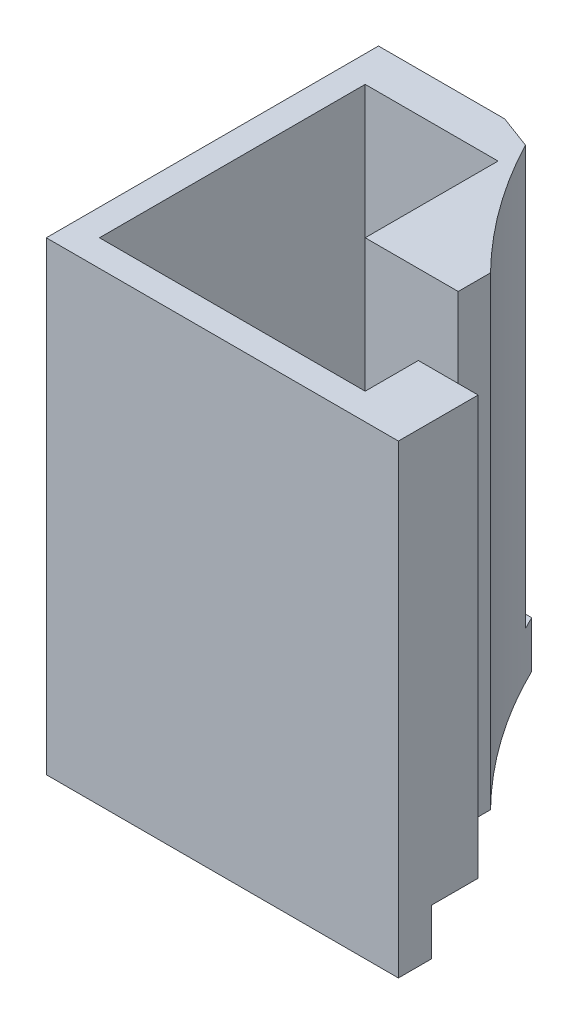
SolidWorks part; units mm, degrees
ref_plane "前视基准面" through (0, 0, 0) normal (0, 0, 1) x (1, 0, 0)
ref_plane "上视基准面" through (0, 0, 0) normal (0, 1, 0) x (1, 0, 0)
ref_plane "右视基准面" through (0, 0, 0) normal (1, 0, 0) x (0, 0, -1)
sketch "草图1" plane through (0, 0, 0) normal (0, 1, 0) x (1, 0, 0)
  line L1 (0, 0) -> (50, 0)
  line L2 (0, 0) -> (0, 50)
  line L3 (0, 50) -> (50, 50)
  line L4 (50, 0) -> (50, 50)
  dimension "D1" = 50
  dimension "D2" = 50
extrude "凸台-拉伸1" add sketch "草图1" along normal blind 7
sketch "草图2" plane through (0, 7, 0) normal (0, 1, 0) x (1, 0, 0)
  line L0 (95, 7) -> (95, 163)
  circle A0 centre (95, 85) radius 80
  dimension "D1" = 160
extrude "切除-拉伸1" cut sketch "草图2" against normal blind 10 contours A0
sketch "草图3" plane through (0, 7, 0) normal (0, 1, 0) x (1, 0, 0)
  line L0 (0, 50) -> (0, 0) construction
  line L1 (38, 35) -> (60, 35)
  line L2 (38, 35) -> (38, 5)
  line L3 (38, 5) -> (60, 5)
  line L4 (60, 35) -> (60, 5)
  line L5 (0, 0) -> (50, 0) construction
  dimension "D1" = 38
  dimension "D2" = 5
  dimension "D3" = 22
  dimension "D4" = 30
extrude "切除-拉伸2" cut sketch "草图3" against normal blind 10
hole_wizard "孔1" positions "草图4" profile "草图5" legacy end condition through all
sketch "草图4" plane through (0, 0, 0) normal (0, -1, 0) x (-1, 0, 0)
  point P0 (-32, 8)
  point P2 (-8, 8)
sketch "草图5" plane through (32, 0, -8) normal (1, 0, 0) x (0, 0, -1)
  line L0 (0, 0) -> (0, 7)
  line L1 (0, 7) -> (1.75, 7)
  line L2 (1.75, 7) -> (1.75, 0)
  line L3 (1.75, 0) -> (0, 0)
  line L4 (0, 110) -> (0, -10) construction
  dimension "直径" = 3.5
  dimension "深度" = 7
hole_wizard "孔2" positions "草图6" profile "草图7" legacy
sketch "草图6" plane through (0, 7, 0) normal (0, 1, 0) x (1, 0, 0)
  point P0 (8, 8)
  point P2 (32, 8)
sketch "草图7" plane through (8, 7, -8) normal (1, 0, 0) x (0, 0, 1)
  line L0 (0, 0) -> (0, 4)
  line L1 (0, 4) -> (3.5, 4)
  line L2 (3.5, 4) -> (3.5, 0)
  line L3 (3.5, 0) -> (0, 0)
  line L4 (0, 110) -> (0, -10) construction
  dimension "直径" = 7
  dimension "深度" = 4
sketch "草图8" plane through (0, 7, 0) normal (0, 1, 0) x (1, 0, 0)
  line L0 (0, 50) -> (0, 0) construction
  line L1 (4, 4) -> (44, 4)
  line L2 (4, 4) -> (4, 24)
  line L3 (4, 24) -> (44, 24)
  line L4 (44, 4) -> (44, 24)
  line L5 (0, 0) -> (50, 0) construction
  line L7 (4, 24) -> (24, 24)
  line L8 (4, 24) -> (4, 44)
  line L9 (4, 44) -> (24, 44)
  line L10 (24, 24) -> (24, 44)
  dimension "D1" = 40
  dimension "D2" = 20
  dimension "D3" = 4
  dimension "D4" = 4
  dimension "D5" = 20
  dimension "D6" = 20
sketch "草图9" plane through (0, 7, 0) normal (0, 1, 0) x (1, 0, 0)
  line L0 (0, 0) -> (50, 0) construction
  line L1 (0, 0) -> (4, 0)
  line L2 (0, 0) -> (0, 50)
  line L3 (0, 50) -> (4, 50)
  line L4 (4, 0) -> (4, 50)
  line L5 (23.0625, 50) -> (0, 50) construction
  line L6 (4, 44) -> (24, 44) construction
  line L7 (4, 0) -> (50, 0)
  line L8 (4, 0) -> (4, 4)
  line L9 (4, 4) -> (50, 4)
  line L10 (50, 0) -> (50, 4)
  line L11 (0, 50) -> (0, 0) construction
  line L12 (50, 0) -> (50, 5) construction
  line L13 (4, 4) -> (44, 4) construction
  line L14 (4, 50) -> (19, 50)
  line L15 (4, 50) -> (4, 44)
  line L16 (4, 44) -> (19, 44)
  line L17 (19, 50) -> (19, 44)
  line L18 (24, 48.1354) -> (24, 24)
  line L19 (24, 24) -> (38, 24)
  line L20 (38, 28.8662) -> (38, 5) construction
  line L21 (38, 24) -> (38, 28.8662)
  line L24 (4, 4) -> (4, 24) construction
  line L26 (24, 24) -> (24, 44) construction
  line L27 (4, 24) -> (44, 24) construction
  circle A1 centre (95, 85) radius 80
  line M15 (38, 5) -> (38, 28.8662)
  arc M16 (38, 28.8662) -> (23.0625, 50) centre (95, 85) cw
  line M17 (23.0625, 50) -> (0, 50)
  line M18 (0, 50) -> (0, 0)
  line M19 (0, 0) -> (50, 0)
  line M20 (50, 0) -> (50, 5)
  dimension "D7" = 160
  dimension "D5" = 95
  dimension "D6" = 85
  dimension "D9" = 15
extrude "凸台-拉伸2" add sketch "草图9" along normal blind 63 contours L17 L4 L16 M17 | L4 M19 M17 M18 | L9 L4 M19 M20 | L18 L19 M15 M16
sketch "草图10" plane through (0, 7, 0) normal (0, 1, 0) x (1, 0, 0)
  line L0 (50, 4) -> (50, 5) construction
  line L1 (50, 4) -> (44, 4)
  line L2 (50, 4) -> (50, 12)
  line L3 (50, 12) -> (44, 12)
  line L4 (44, 4) -> (44, 12)
  line L5 (50, 0) -> (50, 4) construction
  line L7 (4, 4) -> (50, 4) construction
  line L8 (44, 4) -> (44, 24) construction
  dimension "D2" = 8
extrude "凸台-拉伸3" add sketch "草图10" along normal blind 63
sketch "草图11" plane through (0, 7, 0) normal (0, -1, 0) x (1, 0, 0)
  line L1 (44, -5) -> (49, -5)
  line L2 (44, -5) -> (44, -6.5)
  line L3 (44, -6.5) -> (49, -6.5)
  line L4 (49, -5) -> (49, -6.5)
  dimension "D1" = 1.5
  dimension "D2" = 5
extrude "凸台-拉伸4" add sketch "草图11" along normal up to surface (7 mm away) up to face at (32, 0, -9.75)
sketch "草图12" plane through (50, 0, 0) normal (1, 0, 0) x (0, 0, -1)
  line L1 (5, 7) -> (12, 7)
  line L2 (12, 7) -> (12, 70)
  line L3 (12, 70) -> (0, 70)
  line L4 (0, 70) -> (0, 0)
  line L5 (0, 0) -> (5, 0)
  line L7 (5, 7) -> (5, 0)
extrude "凸台-拉伸5" add sketch "草图12" along normal blind 3
sketch "草图13" plane through (0, 0, 0) normal (0, -1, 0) x (-1, 0, 0)
  line L1 (-44, 6.5) -> (-38, 6.5)
  line L2 (-44, 6.5) -> (-44, 5)
  line L3 (-44, 5) -> (-38, 5)
  line L4 (-38, 6.5) -> (-38, 5)
extrude "凸台-拉伸6" add sketch "草图13" against normal up to surface (7 mm away) up to face at (8, 7, -4.5)
sketch "草图15" plane through (0, 7, 0) normal (0, 1, 0) x (1, 0, 0)
  line L0 (19, 44) -> (24, 44)
  line L1 (24, 48.1354) -> (24, 24) construction
  line L2 (24, 44) -> (24, 48.1354)
  line L3 (24, 48.1354) -> (19, 50)
  line L4 (19, 50) -> (19, 44)
extrude "凸台-拉伸7" add sketch "草图15" along normal up to surface (63 mm away) contours L4 L0 L2 L3 up to face at (24, 70, -22)
